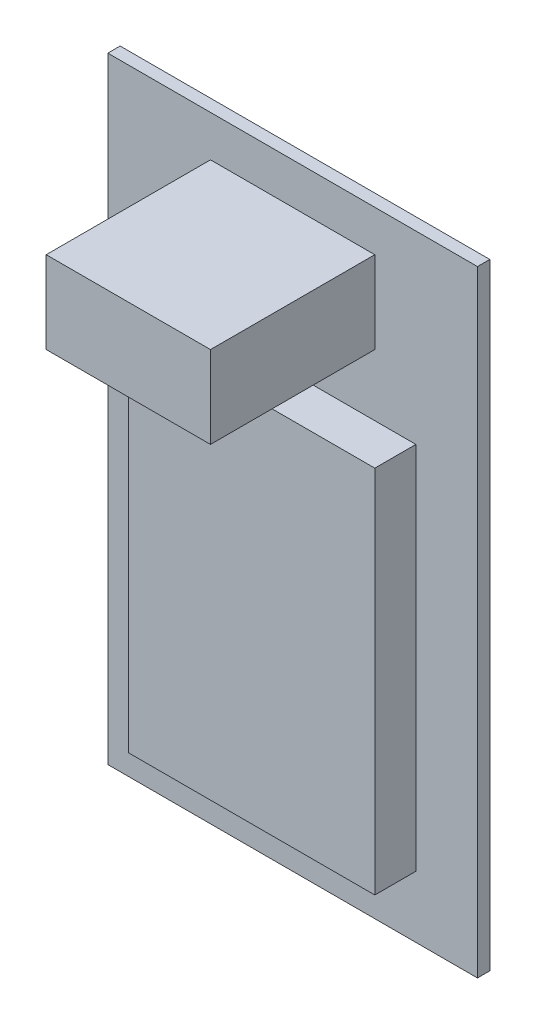
SolidWorks part; units mm, degrees
ref_plane "Front Plane" through (0, 0, 0) normal (1, 0, 0) x (0, 1, 0)
ref_plane "Top Plane" through (0, 0, 0) normal (0, 0, 1) x (0, 1, 0)
ref_plane "Right Plane" through (0, 0, 0) normal (0, 1, 0) x (-1, 0, 0)
sketch "Sketch2" plane through (0, 0, 0) normal (0, 0, 1) x (0, 1, 0)
  line L0 (0, 0) -> (0, 90)
  line L1 (0, 90) -> (150, 90)
  line L2 (150, 90) -> (150, 0)
  line L3 (150, 0) -> (0, 0)
  dimension "D1" = 90
  dimension "D2" = 150
extrude "Boss-Extrude1" add sketch "Sketch2" along normal blind 3
sketch "Sketch3" plane through (0, 0, 3) normal (0, 0, 1) x (1, 0, 0)
  line L0 (-90, 150) -> (-90, 0) construction
  line L1 (-75, 105) -> (-15, 105)
  line L2 (-75, 105) -> (-75, 15)
  line L3 (-75, 15) -> (-15, 15)
  line L4 (-15, 105) -> (-15, 15)
  line L5 (-90, 0) -> (0, 0) construction
  dimension "D1" = 15
  dimension "D2" = 60
  dimension "D3" = 15
  dimension "D4" = 90
extrude "Boss-Extrude2" add sketch "Sketch3" along normal blind 10 contours L1 L4 L3 L2
sketch "Sketch4" plane through (0, 0, 3) normal (0, 0, 1) x (1, 0, 0)
  line L0 (-75, 105) -> (-15, 105) construction
  line L1 (-65, 140) -> (-25, 140)
  line L2 (-65, 140) -> (-65, 120)
  line L3 (-65, 120) -> (-25, 120)
  line L4 (-25, 140) -> (-25, 120)
  line L7 (-90, 150) -> (-90, 0) construction
  dimension "D1" = 15
  dimension "D2" = 20
  dimension "D3" = 40
  dimension "D4" = 25
extrude "Boss-Extrude3" add sketch "Sketch4" along normal blind 40
